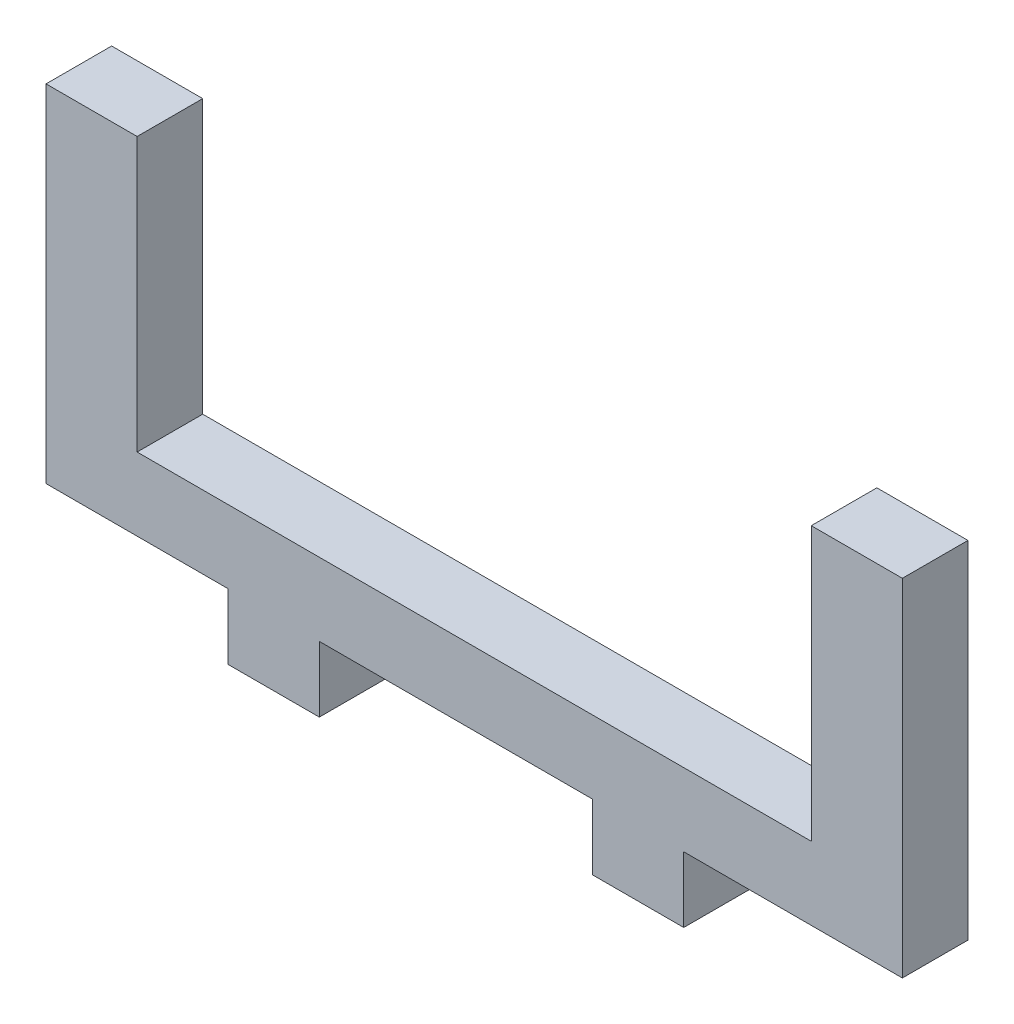
SolidWorks part; units mm, degrees
ref_plane "Front Plane" through (0, 0, 0) normal (0, 0, 1) x (1, 0, 0)
ref_plane "Top Plane" through (0, 0, 0) normal (0, 1, 0) x (1, 0, 0)
ref_plane "Right Plane" through (0, 0, 0) normal (1, 0, 0) x (0, 0, -1)
sketch "Sketch1" plane through (0, 0, 0) normal (0, 0, 1) x (1, 0, 0)
  line L0 (29.845, -5.08) -> (29.845, 19.05) construction
  line L1 (0, 0) -> (6.35, 0)
  line L2 (0, 0) -> (0, 19.05)
  line L3 (0, 19.05) -> (6.35, 19.05)
  line L4 (6.35, 0) -> (6.35, 19.05)
  line L5 (0, 0) -> (59.69, 0)
  line L6 (0, 0) -> (0, -5.08)
  line L7 (0, -5.08) -> (59.69, -5.08)
  line L8 (59.69, 0) -> (59.69, -5.08)
  line L9 (12.7, -5.08) -> (19.05, -5.08)
  line L10 (12.7, -5.08) -> (12.7, -9.652)
  line L11 (12.7, -9.652) -> (19.05, -9.652)
  line L12 (19.05, -5.08) -> (19.05, -9.652)
  line L13 (38.1, -5.08) -> (44.45, -5.08)
  line L14 (38.1, -5.08) -> (38.1, -9.652)
  line L15 (38.1, -9.652) -> (44.45, -9.652)
  line L16 (44.45, -5.08) -> (44.45, -9.652)
  line L17 (59.69, 0) -> (53.34, 0)
  line L18 (59.69, 19.05) -> (53.34, 19.05)
  line L19 (59.69, 0) -> (59.69, 19.05)
  line L20 (53.34, 0) -> (53.34, 19.05)
  dimension "D1" = 19.05
  dimension "D2" = 6.35
  dimension "D3" = 5.08
  dimension "D4" = 6.35
  dimension "D5" = 12.7
  dimension "D6" = 53.34
  dimension "D7" = 19.05
  dimension "D8" = 6.35
  dimension "D9" = 4.572
  dimension "D10" = 4.572
extrude "Boss-Extrude1" add sketch "Sketch1" along normal blind 4.572 contours L7 L0 L5 L1 L6 | L1 L4 L3 L2 | L12 L7 L10 L11 | L0 L7 L8 L5 | L20 L5 L19 L18 | L16 L15 L14 L13
